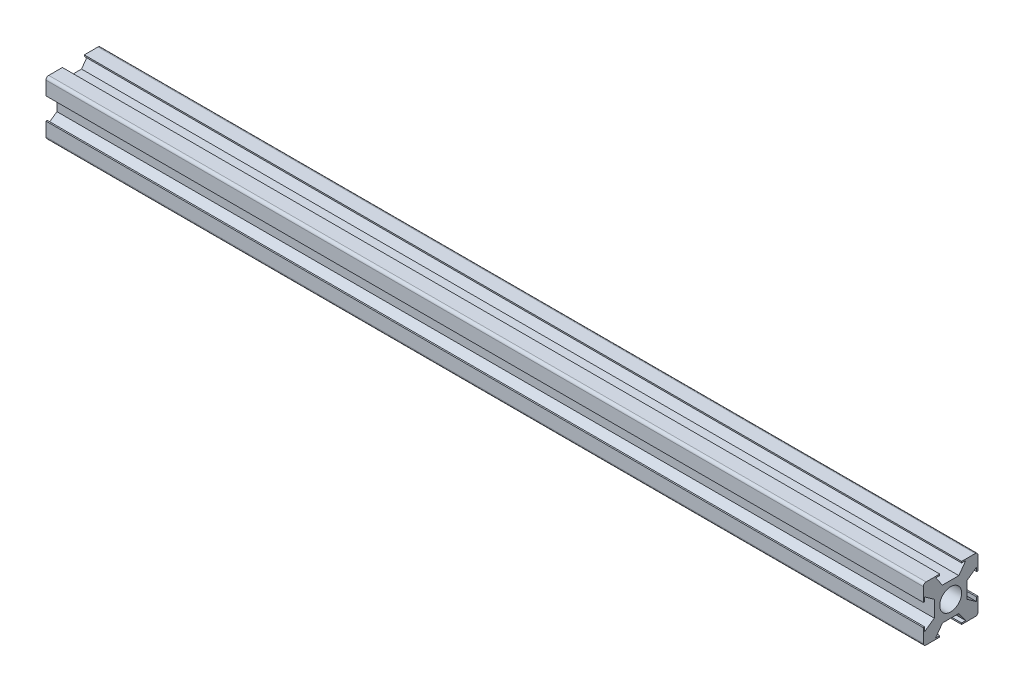
SolidWorks part; units mm, degrees
ref_plane "前视基准面" through (0, 0, 0) normal (0, 0, 1) x (1, 0, 0)
ref_plane "上视基准面" through (0, 0, 0) normal (0, 1, 0) x (1, 0, 0)
ref_plane "右视基准面" through (0, 0, 0) normal (1, 0, 0) x (0, 0, -1)
sketch "草图1" plane through (0, 0, 0) normal (0, 0, 1) x (1, 0, 0)
  line L1 (-66.5187, -1.3979) -> (254.4813, -1.3979)
  line L2 (-66.5187, -1.3979) -> (-66.5187, -11.3979)
  line L3 (-66.5187, -11.3979) -> (254.4813, -11.3979)
  line L4 (254.4813, -1.3979) -> (254.4813, -11.3979)
  dimension "D1" = 10
  dimension "D2" = 321
extrude "凸台-拉伸1" add sketch "草图1" along normal blind 10
sketch "草图2" plane through (254.4813, 0, 0) normal (1, 0, 0) x (0, 0, -1)
  circle A0 centre (0, -11.3979) radius 4
  dimension "D1" = 8
extrude "切除-拉伸1" cut sketch "草图2" against normal blind 1270
sketch "草图3" plane through (254.4813, 0, 0) normal (1, 0, 0) x (0, 0, -1)
  line L0 (-4, -1.3979) -> (0, -1.3979)
  line L1 (-10, -11.3979) -> (-10, -1.3979) construction
  line L2 (-10, -1.3979) -> (0, -1.3979) construction
  line L3 (-10, -7.3979) -> (-10, -11.3979)
  line L4 (-4, -1.3979) -> (-4, -1.8979)
  line L5 (-4, -1.8979) -> (-5.5, -1.8979)
  line L6 (-3, -5.3979) -> (0, -5.3979)
  line L7 (0, -7.3979) -> (0, -1.3979) construction
  line L8 (0, -5.3979) -> (0, -1.3979)
  line L9 (-10, -11.3979) -> (-6, -11.3979)
  line L10 (-10, -11.3979) -> (-4, -11.3979) construction
  line L11 (-6, -11.3979) -> (-6, -8.3979)
  line L12 (-10, -7.3979) -> (-9.5, -7.3979)
  line L13 (-9.5, -7.3979) -> (-9.5, -5.8979)
  line L14 (-5.5, -1.8979) -> (-3, -5.3979)
  line L15 (-9.5, -5.8979) -> (-6, -8.3979)
  dimension "D1" = 4
  dimension "D2" = 4
  dimension "D3" = 4
  dimension "D4" = 4
  dimension "D5" = 0.5
  dimension "D6" = 0.5
  dimension "D7" = 3
  dimension "D8" = 3
  dimension "D9" = 1.5
  dimension "D10" = 1.5
extrude "切除-拉伸2" cut sketch "草图3" against normal blind 1270
fillet "圆角1" radius 1 1 edges at (93.9813, -1.3979, 10)
pattern_circular "阵列(圆周)2" count 4 over 360 about axis through (0, -11.3979, 0) along (1, 0, 0) of "凸台-拉伸1", "圆角1", "切除-拉伸1", "切除-拉伸2"
